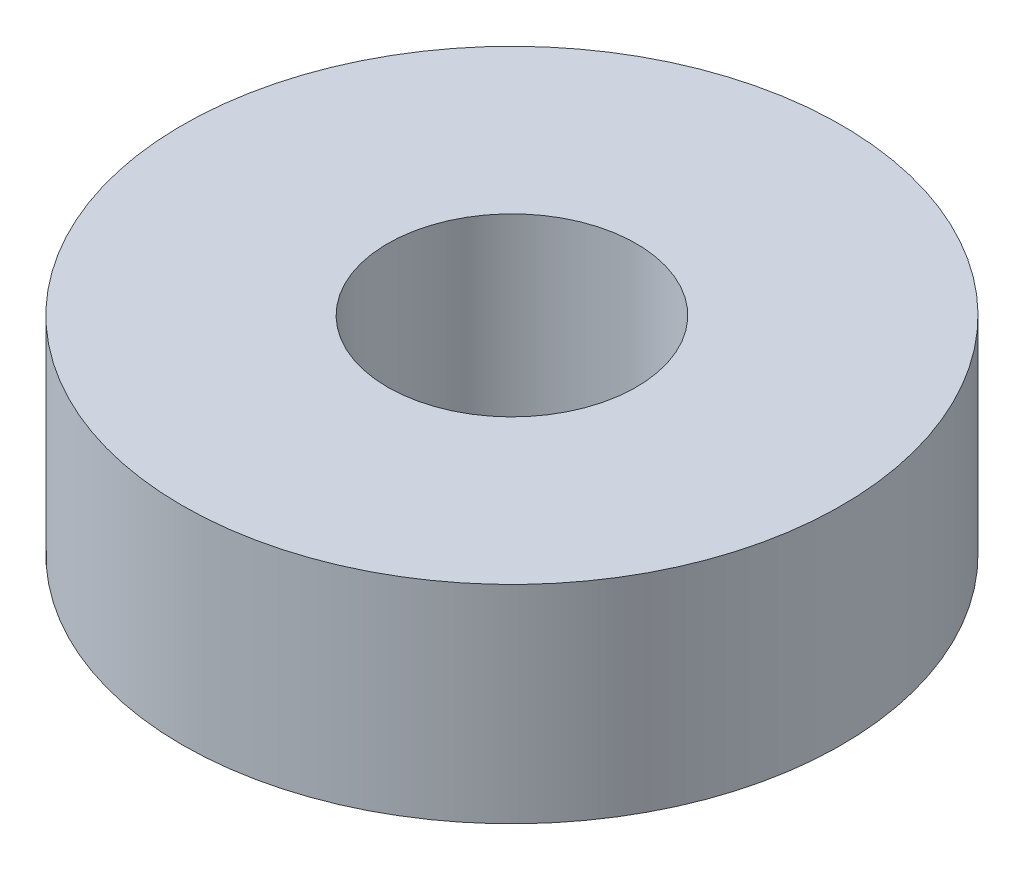
SolidWorks part; units mm, degrees
ref_plane "Front Plane" through (0, 0, 0) normal (0, 0, 1) x (1, 0, 0)
ref_plane "Top Plane" through (0, 0, 0) normal (0, 1, 0) x (1, 0, 0)
ref_plane "Right Plane" through (0, 0, 0) normal (1, 0, 0) x (0, 0, -1)
sketch "Sketch1" plane through (0, 0, 0) normal (0, 1, 0) x (1, 0, 0)
  circle A0 centre (0, 0) radius 7.95
  circle A1 centre (0, 0) radius 3
  dimension "D1" = 6
  dimension "D2" = 15.9
extrude "Boss-Extrude1" add sketch "Sketch1" along normal blind 5
